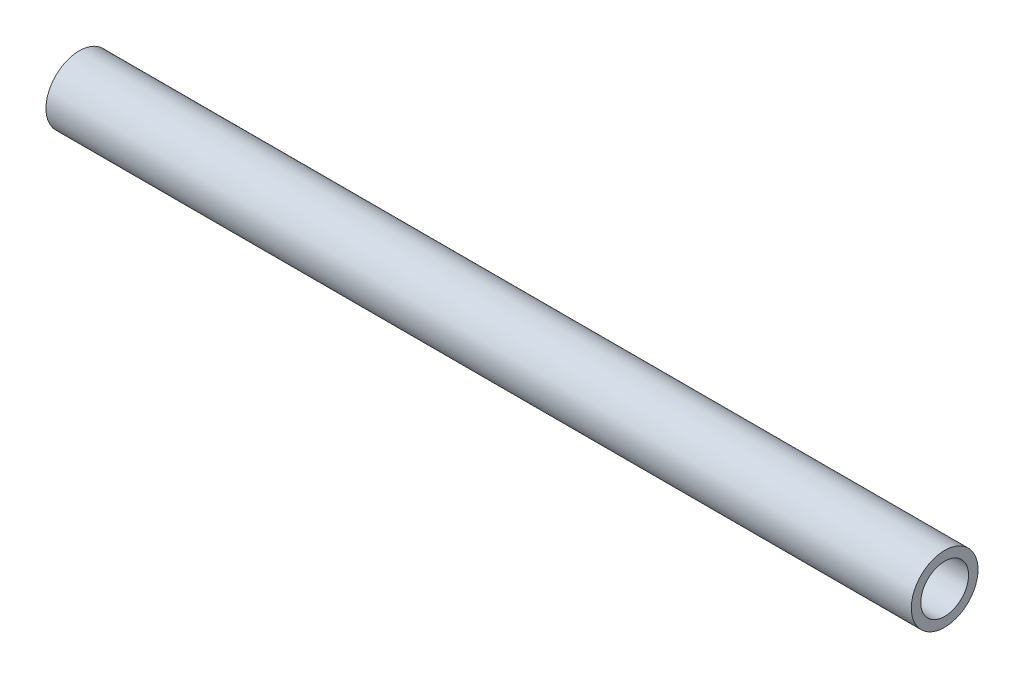
SolidWorks part; units mm, degrees
ref_plane "Front Plane" through (0, 0, 0) normal (0, 0, 1) x (1, 0, 0)
ref_plane "Top Plane" through (0, 0, 0) normal (0, 1, 0) x (1, 0, 0)
ref_plane "Right Plane" through (0, 0, 0) normal (1, 0, 0) x (0, 0, -1)
sketch "Sketch1" plane through (0, 0, 0) normal (1, 0, 0) x (0, 0, -1)
  circle A0 centre (0, 0) radius 10.668
  circle A1 centre (0, 0) radius 7.6454
  dimension "D1" = 21.336
  dimension "D2" = 15.2908
extrude "Boss-Extrude1" add sketch "Sketch1" along normal mid plane 264.16
sketch "Sketch2" plane through (0, 0, 0) normal (0, 1, 0) x (1, 0, 0)
  line L0 (132.08, -10.668) -> (132.08, 10.668) construction
  line L1 (132.08, 10.668) -> (-132.08, 10.668) construction
  circle A0 centre (121.92, 0) radius 2.3876
  circle A1 centre (101.6, 0) radius 2.3876
  circle A2 centre (81.28, 0) radius 2.3876
  circle A3 centre (60.96, 0) radius 2.3876
  circle A4 centre (40.64, 0) radius 2.3876
  circle A5 centre (20.32, 0) radius 2.3876
  circle A6 centre (0, 0) radius 2.3876
  circle A7 centre (-20.32, 0) radius 2.3876
  circle A8 centre (-40.64, 0) radius 2.3876
  circle A9 centre (-60.96, 0) radius 2.3876
  circle A10 centre (-81.28, 0) radius 2.3876
  circle A11 centre (-101.6, 0) radius 2.3876
  circle A12 centre (-121.92, 0) radius 2.3876
  dimension "D1" = 4.7752
  dimension "D2" = 10.16
  dimension "D3" = 10.668
  dimension "D5" = 20.32
  dimension "D4" = 13
extrude "Cut-Extrude1" cut sketch "Sketch2" against normal through all
sketch "Sketch3" plane through (132.08, 0, 0) normal (1, 0, 0) x (0, 0, -1)
  circle A0 centre (0, 0) radius 7.6454 construction
  circle A1 centre (0, 0) radius 10.668
  circle A2 centre (0, 0) radius 10.668
  circle A3 centre (0, 0) radius 7.6454
  dimension "D1" = 0
extrude "Boss-Extrude2" add sketch "Sketch3" along normal blind 6.35
mirror "Mirror1" about plane through (0, 0, 0) normal (1, 0, 0) of "Boss-Extrude2"
